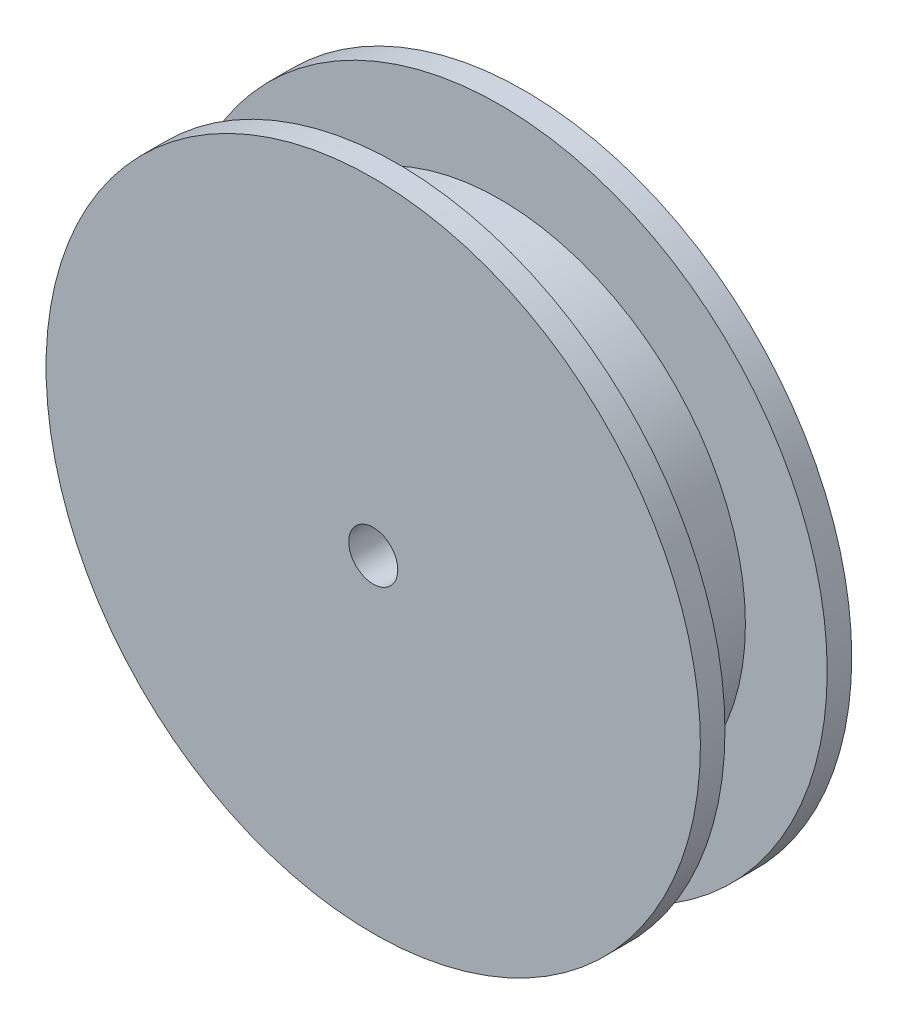
SolidWorks part; units mm, degrees
ref_plane "Front Plane" through (0, 0, 0) normal (0, 0, 1) x (1, 0, 0)
ref_plane "Top Plane" through (0, 0, 0) normal (0, 1, 0) x (1, 0, 0)
ref_plane "Right Plane" through (0, 0, 0) normal (1, 0, 0) x (0, 0, -1)
sketch "Sketch1" plane through (0, 0, 0) normal (0, 0, 1) x (1, 0, 0)
  circle A0 centre (0, 0) radius 30
  circle A1 centre (0, 0) radius 40
  circle A3 centre (0, 0) radius 3
  dimension "D1" = 80
  dimension "D2" = 60
  dimension "D4" = 6
extrude "Boss-Extrude1" add sketch "Sketch1" along normal blind 18.5 contours A1 A0 | A0 A3
ref_plane "Plane1" through (0, 0, 9.25) normal (0, 0, 1) x (1, 0, 0)
sketch "Sketch2" plane through (0, 0, 9.25) normal (0, 0, 1) x (1, 0, 0)
  circle A0 centre (0, 0) radius 30
  circle A1 centre (0, 0) radius 42.5
  dimension "D1" = 60
  dimension "D2" = 85
extrude "Cut-Extrude1" cut sketch "Sketch2" against normal blind 6.25 and the other way blind 6.25 contours A1 A0
